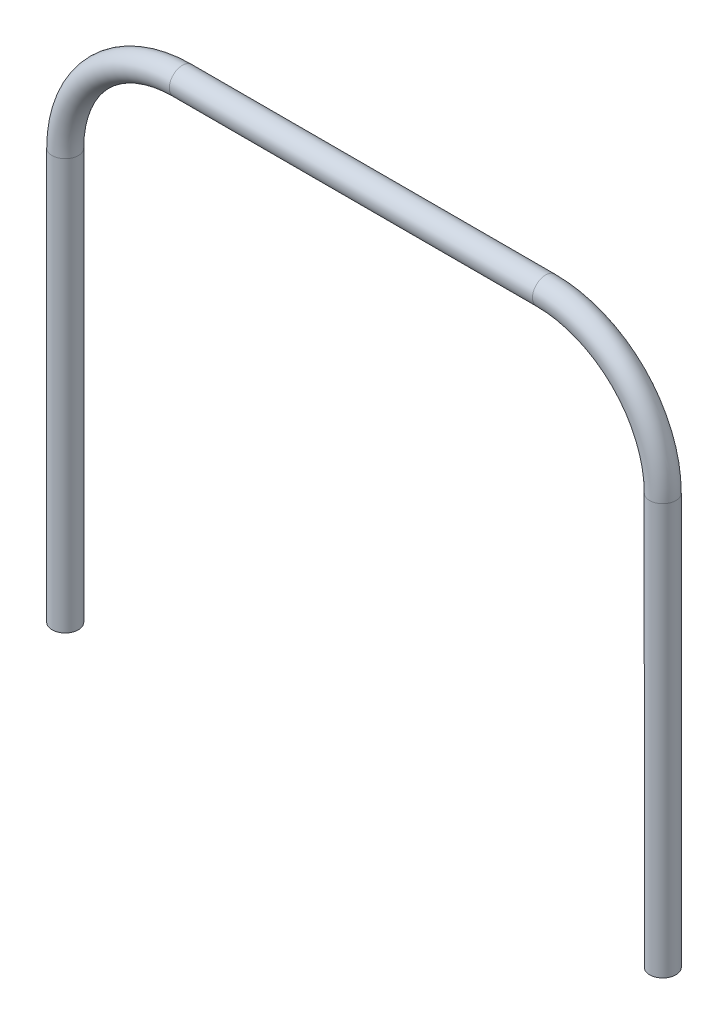
SolidWorks part; units mm, degrees
material "Plain Carbon Steel"
ref_plane "Front Plane" through (0, 0, 0) normal (0, 0, 1) x (1, 0, 0)
ref_plane "Top Plane" through (0, 0, 0) normal (0, 1, 0) x (1, 0, 0)
ref_plane "Right Plane" through (0, 0, 0) normal (1, 0, 0) x (0, 0, -1)
sketch "Sketch1" plane through (0, 0, 0) normal (0, 0, 1) x (1, 0, 0)
  line L0 (0, 0) -> (0, 596)
  line L1 (170, 766) -> (697, 766)
  line L2 (867, 596) -> (867, 0)
  arc A0 (867, 596) -> (697, 766) centre (697, 596) ccw
  arc A1 (170, 766) -> (0, 596) centre (170, 596) ccw
  point P7 (867, 766)
  point P10 (0, 766)
  dimension "D3" = 170
  dimension "D1" = 766
  dimension "D2" = 867
sketch "Sketch2" plane through (0, 0, 0) normal (0, 1, 0) x (1, 0, 0)
  circle A0 centre (0, 0) radius 19
  circle A1 centre (0, 0) radius 17.8
  dimension "D1" = 38
  dimension "D2" = 1.2
sweep "Sweep1" add profiles "Sketch2" path "Sketch1"
